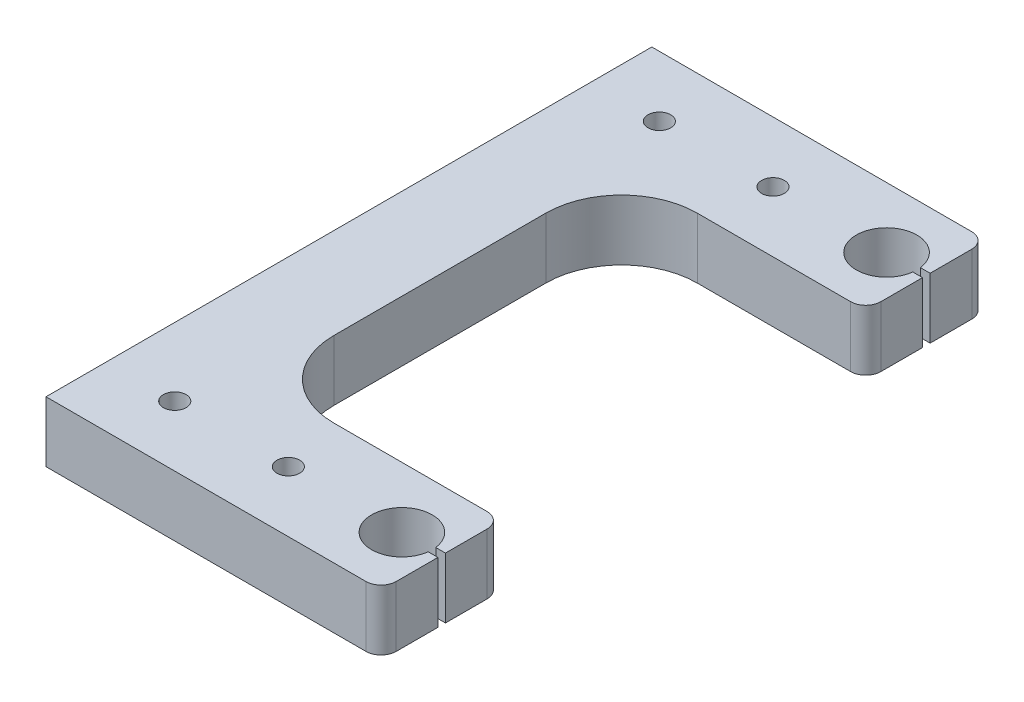
SolidWorks part; units mm, degrees
ref_plane "Front Plane" through (0, 0, 0) normal (0, 0, 1) x (1, 0, 0)
ref_plane "Top Plane" through (0, 0, 0) normal (0, 1, 0) x (1, 0, 0)
ref_plane "Right Plane" through (0, 0, 0) normal (1, 0, 0) x (0, 0, -1)
sketch "Sketch1" plane through (0, 0, 0) normal (0, 1, 0) x (1, 0, 0)
  line L0 (0, 0) -> (0, -80)
  line L1 (0, -80) -> (44.25, -80)
  line L2 (44.25, -80) -> (44.25, -64)
  line L3 (44.25, -64) -> (12, -64)
  line L4 (12, -64) -> (12, -16)
  line L5 (12, -16) -> (44.25, -16)
  line L6 (44.25, -16) -> (44.25, 0)
  line L7 (44.25, 0) -> (0, 0)
  line L8 (0, -40) -> (12, -40) construction
  circle A0 centre (39, -8) radius 4
  circle A1 centre (39, -72) radius 4
  circle A2 centre (24, -8) radius 1.5
  circle A3 centre (9, -8) radius 1.5
  circle A4 centre (24, -72) radius 1.5
  circle A5 centre (9, -72) radius 1.5
  point P15 (22.125, 0)
  dimension "D1" = 8
  dimension "D8" = 3
  dimension "D2" = 32
  dimension "D3" = 39
  dimension "D4" = 16
  dimension "D5" = 5.25
  dimension "D6" = 12
  dimension "D7" = 8
  dimension "D9" = 15
  dimension "D10" = 30
extrude "Boss-Extrude1" add sketch "Sketch1" along normal blind 8
sketch "Sketch4" plane through (0, 8, 0) normal (0, 1, 0) x (1, 0, 0)
  line L0 (39, -8) -> (44.25, -8) construction
  line L1 (44.25, -16) -> (44.25, 0) construction
  line L2 (39, -7.5) -> (44.25, -7.5)
  line L3 (39, -8.5) -> (44.25, -8.5)
  line L4 (39, -72) -> (44.25, -72) construction
  line L5 (44.25, -80) -> (44.25, -64) construction
  line L6 (39, -71.5) -> (44.25, -71.5)
  line L7 (39, -72.5) -> (44.25, -72.5)
  arc A0 (39, -7.5) -> (39, -8.5) centre (39, -8) ccw
  arc A1 (44.25, -8.5) -> (44.25, -7.5) centre (44.25, -8) ccw
  arc A2 (39, -71.5) -> (39, -72.5) centre (39, -72) ccw
  arc A3 (44.25, -72.5) -> (44.25, -71.5) centre (44.25, -72) ccw
  point P5 (41.625, -8)
  point P10 (41.625, -72)
  dimension "D1" = 1
extrude "Cut-Extrude2" cut sketch "Sketch4" against normal through all
fillet "Fillet1" radius 2 4 edges at (44.25, 4, 64) (44.25, 4, 80) (44.25, 4, 0) (44.25, 4, 16)
fillet "Fillet2" radius 10 2 edges at (12, 4, 16) (12, 4, 64)
